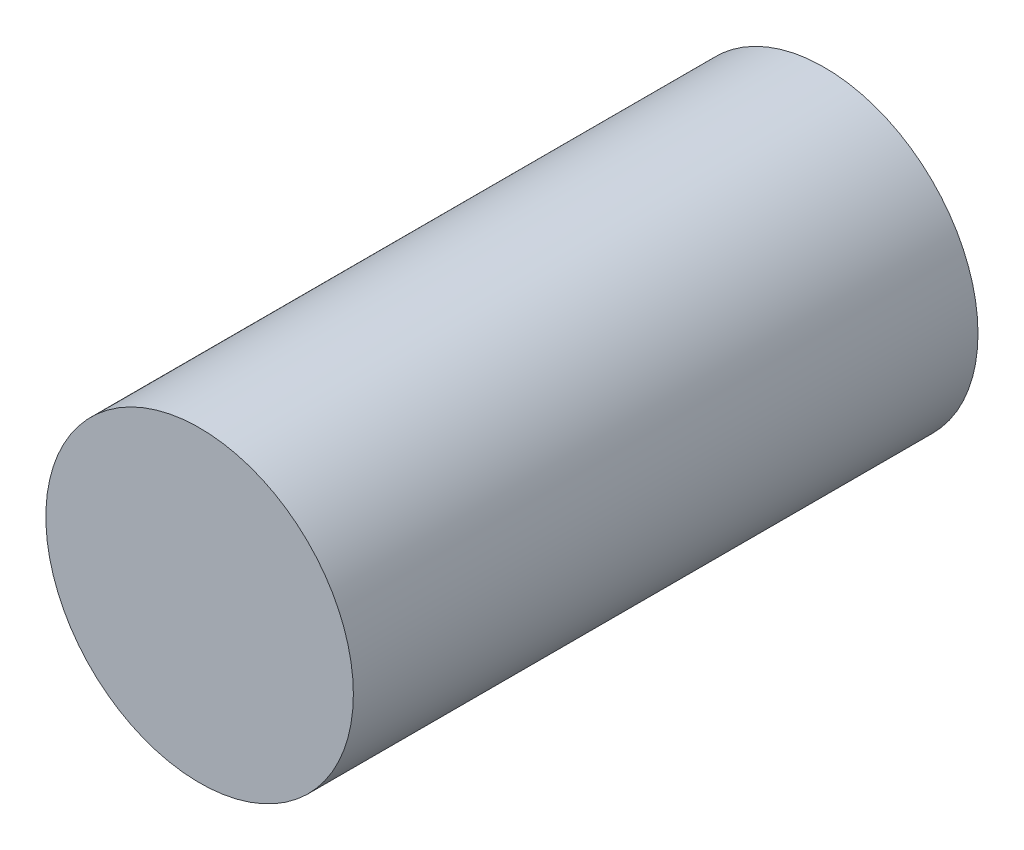
SolidWorks part; units mm, degrees
ref_plane "Front Plane" through (0, 0, 0) normal (0, 0, 1) x (1, 0, 0)
ref_plane "Top Plane" through (0, 0, 0) normal (0, 1, 0) x (1, 0, 0)
ref_plane "Right Plane" through (0, 0, 0) normal (1, 0, 0) x (0, 0, -1)
sketch "Sketch1" plane through (0, 0, 0) normal (0, 0, 1) x (1, 0, 0)
  circle A0 centre (0, 0) radius 16
extrude "Boss-Extrude1" add sketch "Sketch1" along normal blind 65
